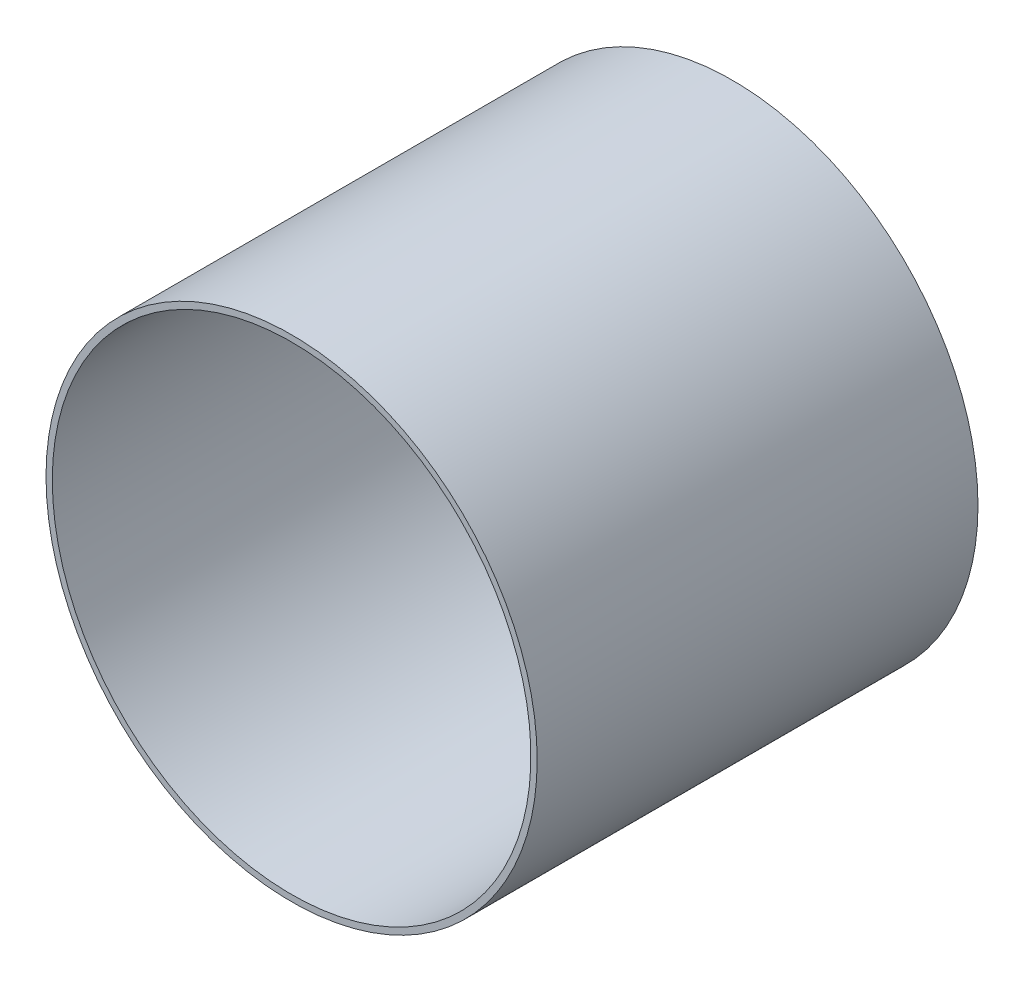
SolidWorks part; units mm, degrees
ref_plane "Front Plane" through (0, 0, 0) normal (0, 0, 1) x (1, 0, 0)
ref_plane "Top Plane" through (0, 0, 0) normal (0, 1, 0) x (1, 0, 0)
ref_plane "Right Plane" through (0, 0, 0) normal (1, 0, 0) x (0, 0, -1)
sketch "Sketch1" plane through (0, 0, 0) normal (0, 1, 0) x (1, 0, 0)
  line L0 (-57.1745, 0) -> (-57.1745, -71.0247) construction
  line L1 (-72.8389, 0) -> (-76.1745, -3.8121)
  line L2 (-76.1745, -3.8121) -> (-76.1745, -7.8121)
  line L3 (-76.1745, -7.8121) -> (-75.6745, -7.8121)
  line L4 (-75.6745, -7.8121) -> (-75.6745, -4)
  line L5 (-75.6745, -4) -> (-72.1745, 0)
  line L6 (-72.1745, 0) -> (-72.8389, 0)
  dimension "D1" = 4
  dimension "D2" = 0.5
  dimension "D3" = 0.5
  dimension "D4" = 4
  dimension "D5" = 38
  dimension "D6" = 30
revolve "Revolve1" add sketch "Sketch1" angle 360 about L0
sketch "Sketch2" plane through (0, 0, 0) normal (0, 0, -1) x (-1, 0, 0)
  circle A0 centre (57.1745, 0) radius 19
  circle A1 centre (57.1745, 0) radius 19.5
  dimension "D1" = 39
extrude "Extrude1" add sketch "Sketch2" against normal blind 35
